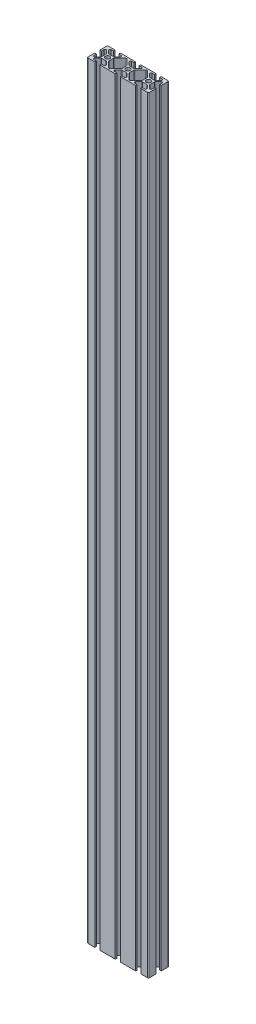
SolidWorks part; units mm, degrees
ref_plane "Front Plane" through (0, 0, 0) normal (0, 0, 1) x (1, 0, 0)
ref_plane "Top Plane" through (0, 0, 0) normal (0, 1, 0) x (1, 0, 0)
ref_plane "Right Plane" through (0, 0, 0) normal (1, 0, 0) x (0, 0, -1)
sketch "Sketch1" plane through (0, 0, 0) normal (0, 1, 0) x (1, 0, 0)
  line L0 (7.5, 20) -> (7.5, 18.5)
  line L1 (1, 0) -> (7.5, 0)
  line L2 (0, 1) -> (0, 7.5)
  line L3 (1, 20) -> (7.5, 20)
  line L4 (60, 1) -> (60, 7.5)
  line L5 (7.5, 18.5) -> (5.0142, 18.5)
  line L6 (4.3071, 16.7929) -> (7.2071, 13.8929)
  line L7 (7.9142, 13.6) -> (12.0858, 13.6)
  line L8 (12.7929, 13.8929) -> (15.6929, 16.7929)
  line L9 (14.9858, 18.5) -> (12.5, 18.5)
  line L10 (12.5, 18.5) -> (12.5, 20)
  line L11 (10, 10) -> (10, 13.6) construction
  line L12 (12.5, 20) -> (27.5, 20)
  line L13 (10, 10) -> (30, 10) construction
  line L14 (12.5, 1.5) -> (12.5, 0)
  line L15 (14.9858, 1.5) -> (12.5, 1.5)
  line L16 (12.7929, 6.1071) -> (15.6929, 3.2071)
  line L17 (7.9142, 6.4) -> (12.0858, 6.4)
  line L18 (4.3071, 3.2071) -> (7.2071, 6.1071)
  line L19 (7.5, 1.5) -> (5.0142, 1.5)
  line L20 (7.5, 0) -> (7.5, 1.5)
  line L21 (12.5, 0) -> (27.5, 0)
  line L22 (27.5, 20) -> (27.5, 18.5)
  line L23 (27.5, 18.5) -> (25.0142, 18.5)
  line L24 (24.3071, 16.7929) -> (27.2071, 13.8929)
  line L25 (27.9142, 13.6) -> (32.0858, 13.6)
  line L26 (32.7929, 13.8929) -> (35.6929, 16.7929)
  line L27 (34.9858, 18.5) -> (32.5, 18.5)
  line L28 (32.5, 18.5) -> (32.5, 20)
  line L29 (32.5, 1.5) -> (32.5, 0)
  line L30 (34.9858, 1.5) -> (32.5, 1.5)
  line L31 (32.7929, 6.1071) -> (35.6929, 3.2071)
  line L32 (27.9142, 6.4) -> (32.0858, 6.4)
  line L33 (24.3071, 3.2071) -> (27.2071, 6.1071)
  line L34 (27.5, 1.5) -> (25.0142, 1.5)
  line L35 (27.5, 0) -> (27.5, 1.5)
  line L36 (47.5, 20) -> (47.5, 18.5)
  line L37 (47.5, 18.5) -> (45.0142, 18.5)
  line L38 (44.3071, 16.7929) -> (47.2071, 13.8929)
  line L39 (47.9142, 13.6) -> (52.0858, 13.6)
  line L40 (52.7929, 13.8929) -> (55.6929, 16.7929)
  line L41 (54.9858, 18.5) -> (52.5, 18.5)
  line L42 (52.5, 18.5) -> (52.5, 20)
  line L43 (52.5, 1.5) -> (52.5, 0)
  line L44 (54.9858, 1.5) -> (52.5, 1.5)
  line L45 (52.7929, 6.1071) -> (55.6929, 3.2071)
  line L46 (47.9142, 6.4) -> (52.0858, 6.4)
  line L47 (44.3071, 3.2071) -> (47.2071, 6.1071)
  line L48 (47.5, 1.5) -> (45.0142, 1.5)
  line L49 (47.5, 0) -> (47.5, 1.5)
  line L50 (32.5, 0) -> (47.5, 0)
  line L51 (52.5, 0) -> (59, 0)
  line L52 (52.5, 20) -> (59, 20)
  line L53 (32.5, 20) -> (47.5, 20)
  line L54 (1.5, 7.5) -> (0, 7.5)
  line L55 (1.5, 5.0142) -> (1.5, 7.5)
  line L56 (6.1071, 7.2071) -> (3.2071, 4.3071)
  line L57 (6.4, 12.0858) -> (6.4, 7.9142)
  line L58 (3.2071, 15.6929) -> (6.1071, 12.7929)
  line L59 (1.5, 12.5) -> (1.5, 14.9858)
  line L60 (0, 12.5) -> (1.5, 12.5)
  line L61 (0, 12.5) -> (0, 19)
  line L62 (30, 10) -> (30, 13.6) construction
  line L63 (60, 12.5) -> (58.5, 12.5)
  line L64 (58.5, 12.5) -> (58.5, 14.9858)
  line L65 (56.7929, 15.6929) -> (53.8929, 12.7929)
  line L66 (53.6, 12.0858) -> (53.6, 7.9142)
  line L67 (53.8929, 7.2071) -> (56.7929, 4.3071)
  line L68 (58.5, 5.0142) -> (58.5, 7.5)
  line L69 (58.5, 7.5) -> (60, 7.5)
  line L70 (60, 12.5) -> (60, 19)
  line L71 (19.2929, 18.1929) -> (13.8929, 12.7929)
  line L72 (13.6, 12.0858) -> (13.6, 7.9142)
  line L73 (13.8929, 7.2071) -> (19.2929, 1.8071)
  line L74 (20.7071, 1.8071) -> (26.1071, 7.2071)
  line L75 (26.4, 7.9142) -> (26.4, 12.0858)
  line L76 (26.1071, 12.7929) -> (20.7071, 18.1929)
  line L77 (20, 1.1) -> (20, 0) construction
  line L78 (33.6, 12.0858) -> (33.6, 7.9142)
  line L79 (33.8929, 7.2071) -> (39.2929, 1.8071)
  line L80 (39.2929, 18.1929) -> (33.8929, 12.7929)
  line L81 (46.1071, 12.7929) -> (40.7071, 18.1929)
  line L82 (46.4, 7.9142) -> (46.4, 12.0858)
  line L83 (40.7071, 1.8071) -> (46.1071, 7.2071)
  circle A0 centre (10, 10) radius 2.15
  circle A1 centre (30, 10) radius 2.15
  circle A2 centre (50, 10) radius 2.15
  arc A3 (12.0858, 13.6) -> (12.7929, 13.8929) centre (12.0858, 14.6) ccw
  arc A4 (7.2071, 13.8929) -> (7.9142, 13.6) centre (7.9142, 14.6) ccw
  arc A5 (15.6929, 16.7929) -> (14.9858, 18.5) centre (14.9858, 17.5) ccw
  arc A6 (5.0142, 18.5) -> (4.3071, 16.7929) centre (5.0142, 17.5) ccw
  arc A7 (5.0142, 1.5) -> (4.3071, 3.2071) centre (5.0142, 2.5) cw
  arc A8 (15.6929, 3.2071) -> (14.9858, 1.5) centre (14.9858, 2.5) cw
  arc A9 (7.2071, 6.1071) -> (7.9142, 6.4) centre (7.9142, 5.4) cw
  arc A10 (12.0858, 6.4) -> (12.7929, 6.1071) centre (12.0858, 5.4) cw
  arc A11 (32.0858, 13.6) -> (32.7929, 13.8929) centre (32.0858, 14.6) ccw
  arc A12 (27.2071, 13.8929) -> (27.9142, 13.6) centre (27.9142, 14.6) ccw
  arc A13 (35.6929, 16.7929) -> (34.9858, 18.5) centre (34.9858, 17.5) ccw
  arc A14 (25.0142, 18.5) -> (24.3071, 16.7929) centre (25.0142, 17.5) ccw
  arc A15 (25.0142, 1.5) -> (24.3071, 3.2071) centre (25.0142, 2.5) cw
  arc A16 (35.6929, 3.2071) -> (34.9858, 1.5) centre (34.9858, 2.5) cw
  arc A17 (27.2071, 6.1071) -> (27.9142, 6.4) centre (27.9142, 5.4) cw
  arc A18 (32.0858, 6.4) -> (32.7929, 6.1071) centre (32.0858, 5.4) cw
  arc A19 (52.0858, 13.6) -> (52.7929, 13.8929) centre (52.0858, 14.6) ccw
  arc A20 (47.2071, 13.8929) -> (47.9142, 13.6) centre (47.9142, 14.6) ccw
  arc A21 (55.6929, 16.7929) -> (54.9858, 18.5) centre (54.9858, 17.5) ccw
  arc A22 (45.0142, 18.5) -> (44.3071, 16.7929) centre (45.0142, 17.5) ccw
  arc A23 (45.0142, 1.5) -> (44.3071, 3.2071) centre (45.0142, 2.5) cw
  arc A24 (55.6929, 3.2071) -> (54.9858, 1.5) centre (54.9858, 2.5) cw
  arc A25 (47.2071, 6.1071) -> (47.9142, 6.4) centre (47.9142, 5.4) cw
  arc A26 (52.0858, 6.4) -> (52.7929, 6.1071) centre (52.0858, 5.4) cw
  arc A27 (1.5, 14.9858) -> (3.2071, 15.6929) centre (2.5, 14.9858) cw
  arc A28 (3.2071, 4.3071) -> (1.5, 5.0142) centre (2.5, 5.0142) cw
  arc A29 (6.1071, 12.7929) -> (6.4, 12.0858) centre (5.4, 12.0858) cw
  arc A30 (6.4, 7.9142) -> (6.1071, 7.2071) centre (5.4, 7.9142) cw
  arc A31 (53.6, 7.9142) -> (53.8929, 7.2071) centre (54.6, 7.9142) ccw
  arc A32 (53.8929, 12.7929) -> (53.6, 12.0858) centre (54.6, 12.0858) ccw
  arc A33 (56.7929, 4.3071) -> (58.5, 5.0142) centre (57.5, 5.0142) ccw
  arc A34 (58.5, 14.9858) -> (56.7929, 15.6929) centre (57.5, 14.9858) ccw
  arc A35 (13.8929, 12.7929) -> (13.6, 12.0858) centre (14.6, 12.0858) ccw
  arc A36 (13.6, 7.9142) -> (13.8929, 7.2071) centre (14.6, 7.9142) ccw
  arc A37 (19.2929, 1.8071) -> (20.7071, 1.8071) centre (20, 2.5142) ccw
  arc A38 (26.1071, 7.2071) -> (26.4, 7.9142) centre (25.4, 7.9142) ccw
  arc A39 (26.4, 12.0858) -> (26.1071, 12.7929) centre (25.4, 12.0858) ccw
  arc A40 (19.2929, 18.1929) -> (20.7071, 18.1929) centre (20, 17.4858) cw
  arc A41 (33.6, 7.9142) -> (33.8929, 7.2071) centre (34.6, 7.9142) ccw
  arc A42 (33.8929, 12.7929) -> (33.6, 12.0858) centre (34.6, 12.0858) ccw
  arc A43 (39.2929, 18.1929) -> (40.7071, 18.1929) centre (40, 17.4858) cw
  arc A44 (46.4, 12.0858) -> (46.1071, 12.7929) centre (45.4, 12.0858) ccw
  arc A45 (46.1071, 7.2071) -> (46.4, 7.9142) centre (45.4, 7.9142) ccw
  arc A46 (39.2929, 1.8071) -> (40.7071, 1.8071) centre (40, 2.5142) ccw
  arc A47 (0, 19) -> (1, 20) centre (1, 19) cw
  arc A48 (1, 0) -> (0, 1) centre (1, 1) cw
  arc A49 (59, 0) -> (60, 1) centre (59, 1) ccw
  arc A50 (59, 20) -> (60, 19) centre (59, 19) cw
  point P24 (7.5, 13.6)
  point P45 (7.5, 6.4)
  point P80 (27.5, 6.4)
  point P113 (47.5, 6.4)
  point P130 (6.4, 12.5)
  point P131 (10, 10)
  point P147 (53.6, 12.5)
  point P157 (13.6, 12.5)
  point P160 (13.6, 7.5)
  point P166 (26.4, 7.5)
  point P169 (26.4, 12.5)
  point P172 (20, 18.9)
  point P195 (0, 0)
  dimension "D3" = 4.3
  dimension "D7" = 1.5
  dimension "D14" = 1
  dimension "D20" = 1
  dimension "D23" = 1
  dimension "D1" = 60
  dimension "D2" = 3
  dimension "D4" = 10
  dimension "D5" = 10
  dimension "D8" = 5
  dimension "D9" = 2.5
  dimension "D10" = 6.4
  dimension "D11" = 1.5
  dimension "D12" = 45
  dimension "D13" = 90
  dimension "D15" = 5
  dimension "D17" = 7.5
  dimension "D18" = 7.2
  dimension "D19" = 6.4
  dimension "D22" = 7.2
  dimension "D6" = 3
  dimension "D21" = 2
  dimension "D16" = 2
extrude "Boss-Extrude1" add sketch "Sketch1" along normal blind 750
